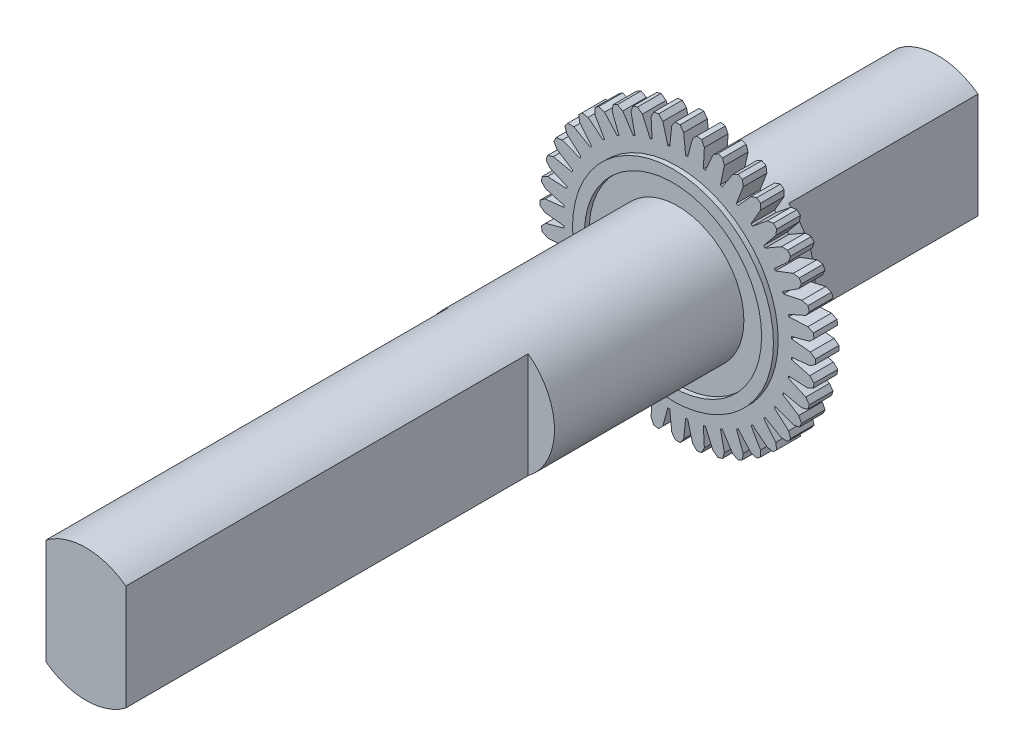
SolidWorks part; units mm, degrees
ref_plane "Front Plane" through (0, 0, 0) normal (0, 0, 1) x (1, 0, 0)
ref_plane "Top Plane" through (0, 0, 0) normal (0, 1, 0) x (1, 0, 0)
ref_plane "Right Plane" through (0, 0, 0) normal (1, 0, 0) x (0, 0, -1)
sketch "Sketch1" plane through (0, 0, 0) normal (0, 0, 1) x (1, 0, 0)
  line L0 (0, 0) -> (0, 5.815) construction
  line L1 (0, 0) -> (0.3359, 4.8033) construction
  line L2 (1.0098, 5.7267) -> (1.1251, 5.4958)
  line L3 (0.1015, 5.8141) -> (0.2515, 5.6041)
  line L4 (0.2515, 5.6041) -> (0.3359, 4.8033)
  line L5 (-0.2515, 5.6041) -> (-0.3359, 4.8033)
  line L6 (-0.1015, 5.8141) -> (-0.2515, 5.6041)
  line L7 (1.1251, 5.4958) -> (1.0831, 4.6916)
  line L8 (0.6283, 5.5745) -> (0.4197, 4.7967)
  line L9 (0.8093, 5.7584) -> (0.6283, 5.5745)
  line L10 (1.8932, 5.4982) -> (1.9709, 5.2521)
  line L11 (1.9709, 5.2521) -> (1.8037, 4.4644)
  line L12 (1.4926, 5.4075) -> (1.1649, 4.672)
  line L13 (1.7001, 5.5609) -> (1.4926, 5.4075)
  line L14 (2.73, 5.1343) -> (2.7683, 4.8791)
  line L15 (2.7683, 4.8791) -> (2.4799, 4.1273)
  line L16 (2.3201, 5.1075) -> (1.8814, 4.4322)
  line L17 (2.5491, 5.2265) -> (2.3201, 5.1075)
  line L18 (3.4996, 4.6441) -> (3.4975, 4.386)
  line L19 (3.4975, 4.386) -> (3.095, 3.6885)
  line L20 (3.0906, 4.6816) -> (2.5516, 4.0834)
  line L21 (3.3353, 4.7634) -> (3.0906, 4.6816)
  line L22 (4.183, 4.0394) -> (4.1405, 3.7849)
  line L23 (4.1405, 3.7849) -> (3.6339, 3.1589)
  line L24 (3.7849, 4.1405) -> (3.1589, 3.6339)
  line L25 (4.0394, 4.183) -> (3.7849, 4.1405)
  line L26 (4.7634, 3.3353) -> (4.6816, 3.0906)
  line L27 (4.6816, 3.0906) -> (4.0834, 2.5516)
  line L28 (4.386, 3.4975) -> (3.6885, 3.095)
  line L29 (4.6441, 3.4996) -> (4.386, 3.4975)
  line L30 (5.2265, 2.5491) -> (5.1075, 2.3201)
  line L31 (5.1075, 2.3201) -> (4.4322, 1.8814)
  line L32 (4.8791, 2.7683) -> (4.1273, 2.4799)
  line L33 (5.1343, 2.73) -> (4.8791, 2.7683)
  line L34 (5.5609, 1.7001) -> (5.4075, 1.4926)
  line L35 (5.4075, 1.4926) -> (4.672, 1.1649)
  line L36 (5.2521, 1.9709) -> (4.4644, 1.8037)
  line L37 (5.4982, 1.8932) -> (5.2521, 1.9709)
  line L38 (5.7584, 0.8093) -> (5.5745, 0.6283)
  line L39 (5.5745, 0.6283) -> (4.7967, 0.4197)
  line L40 (5.4958, 1.1251) -> (4.6916, 1.0831)
  line L41 (5.7267, 1.0098) -> (5.4958, 1.1251)
  line L42 (5.8141, -0.1015) -> (5.6041, -0.2515)
  line L43 (5.6041, -0.2515) -> (4.8033, -0.3359)
  line L44 (5.6041, 0.2515) -> (4.8033, 0.3359)
  line L45 (5.8141, 0.1015) -> (5.6041, 0.2515)
  line L46 (5.7267, -1.0098) -> (5.4958, -1.1251)
  line L47 (5.4958, -1.1251) -> (4.6916, -1.0831)
  line L48 (5.5745, -0.6283) -> (4.7967, -0.4197)
  line L49 (5.7584, -0.8093) -> (5.5745, -0.6283)
  line L50 (5.4982, -1.8932) -> (5.2521, -1.9709)
  line L51 (5.2521, -1.9709) -> (4.4644, -1.8037)
  line L52 (5.4075, -1.4926) -> (4.672, -1.1649)
  line L53 (5.5609, -1.7001) -> (5.4075, -1.4926)
  line L54 (5.1343, -2.73) -> (4.8791, -2.7683)
  line L55 (4.8791, -2.7683) -> (4.1273, -2.4799)
  line L56 (5.1075, -2.3201) -> (4.4322, -1.8814)
  line L57 (5.2265, -2.5491) -> (5.1075, -2.3201)
  line L58 (4.6441, -3.4996) -> (4.386, -3.4975)
  line L59 (4.386, -3.4975) -> (3.6885, -3.095)
  line L60 (4.6816, -3.0906) -> (4.0834, -2.5516)
  line L61 (4.7634, -3.3353) -> (4.6816, -3.0906)
  line L62 (4.0394, -4.183) -> (3.7849, -4.1405)
  line L63 (3.7849, -4.1405) -> (3.1589, -3.6339)
  line L64 (4.1405, -3.7849) -> (3.6339, -3.1589)
  line L65 (4.183, -4.0394) -> (4.1405, -3.7849)
  line L66 (3.3353, -4.7634) -> (3.0906, -4.6816)
  line L67 (3.0906, -4.6816) -> (2.5516, -4.0834)
  line L68 (3.4975, -4.386) -> (3.095, -3.6885)
  line L69 (3.4996, -4.6441) -> (3.4975, -4.386)
  line L70 (2.5491, -5.2265) -> (2.3201, -5.1075)
  line L71 (2.3201, -5.1075) -> (1.8814, -4.4322)
  line L72 (2.7683, -4.8791) -> (2.4799, -4.1273)
  line L73 (2.73, -5.1343) -> (2.7683, -4.8791)
  line L74 (1.7001, -5.5609) -> (1.4926, -5.4075)
  line L75 (1.4926, -5.4075) -> (1.1649, -4.672)
  line L76 (1.9709, -5.2521) -> (1.8037, -4.4644)
  line L77 (1.8932, -5.4982) -> (1.9709, -5.2521)
  line L78 (0.8093, -5.7584) -> (0.6283, -5.5745)
  line L79 (0.6283, -5.5745) -> (0.4197, -4.7967)
  line L80 (1.1251, -5.4958) -> (1.0831, -4.6916)
  line L81 (1.0098, -5.7267) -> (1.1251, -5.4958)
  line L82 (-0.1015, -5.8141) -> (-0.2515, -5.6041)
  line L83 (-0.2515, -5.6041) -> (-0.3359, -4.8033)
  line L84 (0.2515, -5.6041) -> (0.3359, -4.8033)
  line L85 (0.1015, -5.8141) -> (0.2515, -5.6041)
  line L86 (-1.0098, -5.7267) -> (-1.1251, -5.4958)
  line L87 (-1.1251, -5.4958) -> (-1.0831, -4.6916)
  line L88 (-0.6283, -5.5745) -> (-0.4197, -4.7967)
  line L89 (-0.8093, -5.7584) -> (-0.6283, -5.5745)
  line L90 (-1.8932, -5.4982) -> (-1.9709, -5.2521)
  line L91 (-1.9709, -5.2521) -> (-1.8037, -4.4644)
  line L92 (-1.4926, -5.4075) -> (-1.1649, -4.672)
  line L93 (-1.7001, -5.5609) -> (-1.4926, -5.4075)
  line L94 (-2.73, -5.1343) -> (-2.7683, -4.8791)
  line L95 (-2.7683, -4.8791) -> (-2.4799, -4.1273)
  line L96 (-2.3201, -5.1075) -> (-1.8814, -4.4322)
  line L97 (-2.5491, -5.2265) -> (-2.3201, -5.1075)
  line L98 (-3.4996, -4.6441) -> (-3.4975, -4.386)
  line L99 (-3.4975, -4.386) -> (-3.095, -3.6885)
  line L100 (-3.0906, -4.6816) -> (-2.5516, -4.0834)
  line L101 (-3.3353, -4.7634) -> (-3.0906, -4.6816)
  line L102 (-4.183, -4.0394) -> (-4.1405, -3.7849)
  line L103 (-4.1405, -3.7849) -> (-3.6339, -3.1589)
  line L104 (-3.7849, -4.1405) -> (-3.1589, -3.6339)
  line L105 (-4.0394, -4.183) -> (-3.7849, -4.1405)
  line L106 (-4.7634, -3.3353) -> (-4.6816, -3.0906)
  line L107 (-4.6816, -3.0906) -> (-4.0834, -2.5516)
  line L108 (-4.386, -3.4975) -> (-3.6885, -3.095)
  line L109 (-4.6441, -3.4996) -> (-4.386, -3.4975)
  line L110 (-5.2265, -2.5491) -> (-5.1075, -2.3201)
  line L111 (-5.1075, -2.3201) -> (-4.4322, -1.8814)
  line L112 (-4.8791, -2.7683) -> (-4.1273, -2.4799)
  line L113 (-5.1343, -2.73) -> (-4.8791, -2.7683)
  line L114 (-5.5609, -1.7001) -> (-5.4075, -1.4926)
  line L115 (-5.4075, -1.4926) -> (-4.672, -1.1649)
  line L116 (-5.2521, -1.9709) -> (-4.4644, -1.8037)
  line L117 (-5.4982, -1.8932) -> (-5.2521, -1.9709)
  line L118 (-5.7584, -0.8093) -> (-5.5745, -0.6283)
  line L119 (-5.5745, -0.6283) -> (-4.7967, -0.4197)
  line L120 (-5.4958, -1.1251) -> (-4.6916, -1.0831)
  line L121 (-5.7267, -1.0098) -> (-5.4958, -1.1251)
  line L122 (-5.8141, 0.1015) -> (-5.6041, 0.2515)
  line L123 (-5.6041, 0.2515) -> (-4.8033, 0.3359)
  line L124 (-5.6041, -0.2515) -> (-4.8033, -0.3359)
  line L125 (-5.8141, -0.1015) -> (-5.6041, -0.2515)
  line L126 (-5.7267, 1.0098) -> (-5.4958, 1.1251)
  line L127 (-5.4958, 1.1251) -> (-4.6916, 1.0831)
  line L128 (-5.5745, 0.6283) -> (-4.7967, 0.4197)
  line L129 (-5.7584, 0.8093) -> (-5.5745, 0.6283)
  line L130 (-5.4982, 1.8932) -> (-5.2521, 1.9709)
  line L131 (-5.2521, 1.9709) -> (-4.4644, 1.8037)
  line L132 (-5.4075, 1.4926) -> (-4.672, 1.1649)
  line L133 (-5.5609, 1.7001) -> (-5.4075, 1.4926)
  line L134 (-5.1343, 2.73) -> (-4.8791, 2.7683)
  line L135 (-4.8791, 2.7683) -> (-4.1273, 2.4799)
  line L136 (-5.1075, 2.3201) -> (-4.4322, 1.8814)
  line L137 (-5.2265, 2.5491) -> (-5.1075, 2.3201)
  line L138 (-4.6441, 3.4996) -> (-4.386, 3.4975)
  line L139 (-4.386, 3.4975) -> (-3.6885, 3.095)
  line L140 (-4.6816, 3.0906) -> (-4.0834, 2.5516)
  line L141 (-4.7634, 3.3353) -> (-4.6816, 3.0906)
  line L142 (-4.0394, 4.183) -> (-3.7849, 4.1405)
  line L143 (-3.7849, 4.1405) -> (-3.1589, 3.6339)
  line L144 (-4.1405, 3.7849) -> (-3.6339, 3.1589)
  line L145 (-4.183, 4.0394) -> (-4.1405, 3.7849)
  line L146 (-3.3353, 4.7634) -> (-3.0906, 4.6816)
  line L147 (-3.0906, 4.6816) -> (-2.5516, 4.0834)
  line L148 (-3.4975, 4.386) -> (-3.095, 3.6885)
  line L149 (-3.4996, 4.6441) -> (-3.4975, 4.386)
  line L150 (-2.5491, 5.2265) -> (-2.3201, 5.1075)
  line L151 (-2.3201, 5.1075) -> (-1.8814, 4.4322)
  line L152 (-2.7683, 4.8791) -> (-2.4799, 4.1273)
  line L153 (-2.73, 5.1343) -> (-2.7683, 4.8791)
  line L154 (-1.7001, 5.5609) -> (-1.4926, 5.4075)
  line L155 (-1.4926, 5.4075) -> (-1.1649, 4.672)
  line L156 (-1.9709, 5.2521) -> (-1.8037, 4.4644)
  line L157 (-1.8932, 5.4982) -> (-1.9709, 5.2521)
  line L158 (-0.8093, 5.7584) -> (-0.6283, 5.5745)
  line L159 (-0.6283, 5.5745) -> (-0.4197, 4.7967)
  line L160 (-1.1251, 5.4958) -> (-1.0831, 4.6916)
  line L161 (-1.0098, 5.7267) -> (-1.1251, 5.4958)
  arc A0 (0.1015, 5.8141) -> (-0.1015, 5.8141) centre (0, 0) ccw
  arc A1 (-2.4799, 4.1273) -> (-2.5516, 4.0834) centre (0, 0) ccw
  arc A2 (1.0098, 5.7267) -> (0.8093, 5.7584) centre (0, 0) ccw
  circle A3 centre (0, 0) radius 5.815 construction
  arc A4 (1.8932, 5.4982) -> (1.7001, 5.5609) centre (0, 0) ccw
  arc A5 (2.73, 5.1343) -> (2.5491, 5.2265) centre (0, 0) ccw
  arc A6 (3.4996, 4.6441) -> (3.3353, 4.7634) centre (0, 0) ccw
  arc A7 (4.183, 4.0394) -> (4.0394, 4.183) centre (0, 0) ccw
  arc A8 (4.7634, 3.3353) -> (4.6441, 3.4996) centre (0, 0) ccw
  arc A9 (5.2265, 2.5491) -> (5.1343, 2.73) centre (0, 0) ccw
  arc A10 (5.5609, 1.7001) -> (5.4982, 1.8932) centre (0, 0) ccw
  arc A11 (5.7584, 0.8093) -> (5.7267, 1.0098) centre (0, 0) ccw
  arc A12 (5.8141, -0.1015) -> (5.8141, 0.1015) centre (0, 0) ccw
  arc A13 (5.7267, -1.0098) -> (5.7584, -0.8093) centre (0, 0) ccw
  arc A14 (5.4982, -1.8932) -> (5.5609, -1.7001) centre (0, 0) ccw
  arc A15 (5.1343, -2.73) -> (5.2265, -2.5491) centre (0, 0) ccw
  arc A16 (4.6441, -3.4996) -> (4.7634, -3.3353) centre (0, 0) ccw
  arc A17 (4.0394, -4.183) -> (4.183, -4.0394) centre (0, 0) ccw
  arc A18 (3.3353, -4.7634) -> (3.4996, -4.6441) centre (0, 0) ccw
  arc A19 (2.5491, -5.2265) -> (2.73, -5.1343) centre (0, 0) ccw
  arc A20 (1.7001, -5.5609) -> (1.8932, -5.4982) centre (0, 0) ccw
  arc A21 (0.8093, -5.7584) -> (1.0098, -5.7267) centre (0, 0) ccw
  arc A22 (-0.1015, -5.8141) -> (0.1015, -5.8141) centre (0, 0) ccw
  arc A23 (-1.0098, -5.7267) -> (-0.8093, -5.7584) centre (0, 0) ccw
  arc A24 (-1.8932, -5.4982) -> (-1.7001, -5.5609) centre (0, 0) ccw
  arc A25 (-2.73, -5.1343) -> (-2.5491, -5.2265) centre (0, 0) ccw
  arc A26 (-3.4996, -4.6441) -> (-3.3353, -4.7634) centre (0, 0) ccw
  arc A27 (-4.183, -4.0394) -> (-4.0394, -4.183) centre (0, 0) ccw
  arc A28 (-4.7634, -3.3353) -> (-4.6441, -3.4996) centre (0, 0) ccw
  arc A29 (-5.2265, -2.5491) -> (-5.1343, -2.73) centre (0, 0) ccw
  arc A30 (-5.5609, -1.7001) -> (-5.4982, -1.8932) centre (0, 0) ccw
  arc A31 (-5.7584, -0.8093) -> (-5.7267, -1.0098) centre (0, 0) ccw
  arc A32 (-5.8141, 0.1015) -> (-5.8141, -0.1015) centre (0, 0) ccw
  arc A33 (-5.7267, 1.0098) -> (-5.7584, 0.8093) centre (0, 0) ccw
  arc A34 (-5.4982, 1.8932) -> (-5.5609, 1.7001) centre (0, 0) ccw
  arc A35 (-5.1343, 2.73) -> (-5.2265, 2.5491) centre (0, 0) ccw
  arc A36 (-4.6441, 3.4996) -> (-4.7634, 3.3353) centre (0, 0) ccw
  arc A37 (-4.0394, 4.183) -> (-4.183, 4.0394) centre (0, 0) ccw
  arc A38 (-3.3353, 4.7634) -> (-3.4996, 4.6441) centre (0, 0) ccw
  arc A39 (-2.5491, 5.2265) -> (-2.73, 5.1343) centre (0, 0) ccw
  arc A40 (-1.7001, 5.5609) -> (-1.8932, 5.4982) centre (0, 0) ccw
  arc A41 (-0.8093, 5.7584) -> (-1.0098, 5.7267) centre (0, 0) ccw
  arc A42 (-1.8037, 4.4644) -> (-1.8814, 4.4322) centre (0, 0) ccw
  circle A43 centre (0, 0) radius 4.815 construction
  arc A44 (-1.0831, 4.6916) -> (-1.1649, 4.672) centre (0, 0) ccw
  arc A45 (-0.3359, 4.8033) -> (-0.4197, 4.7967) centre (0, 0) ccw
  arc A46 (0.4197, 4.7967) -> (0.3359, 4.8033) centre (0, 0) ccw
  arc A47 (1.1649, 4.672) -> (1.0831, 4.6916) centre (0, 0) ccw
  arc A48 (1.8814, 4.4322) -> (1.8037, 4.4644) centre (0, 0) ccw
  arc A49 (2.5516, 4.0834) -> (2.4799, 4.1273) centre (0, 0) ccw
  arc A50 (3.1589, 3.6339) -> (3.095, 3.6885) centre (0, 0) ccw
  arc A51 (3.6885, 3.095) -> (3.6339, 3.1589) centre (0, 0) ccw
  arc A52 (4.1273, 2.4799) -> (4.0834, 2.5516) centre (0, 0) ccw
  arc A53 (4.4644, 1.8037) -> (4.4322, 1.8814) centre (0, 0) ccw
  arc A54 (4.6916, 1.0831) -> (4.672, 1.1649) centre (0, 0) ccw
  arc A55 (4.8033, 0.3359) -> (4.7967, 0.4197) centre (0, 0) ccw
  arc A56 (4.7967, -0.4197) -> (4.8033, -0.3359) centre (0, 0) ccw
  arc A57 (4.672, -1.1649) -> (4.6916, -1.0831) centre (0, 0) ccw
  arc A58 (4.4322, -1.8814) -> (4.4644, -1.8037) centre (0, 0) ccw
  arc A59 (4.0834, -2.5516) -> (4.1273, -2.4799) centre (0, 0) ccw
  arc A60 (3.6339, -3.1589) -> (3.6885, -3.095) centre (0, 0) ccw
  arc A61 (3.095, -3.6885) -> (3.1589, -3.6339) centre (0, 0) ccw
  arc A62 (2.4799, -4.1273) -> (2.5516, -4.0834) centre (0, 0) ccw
  arc A63 (1.8037, -4.4644) -> (1.8814, -4.4322) centre (0, 0) ccw
  arc A64 (1.0831, -4.6916) -> (1.1649, -4.672) centre (0, 0) ccw
  arc A65 (0.3359, -4.8033) -> (0.4197, -4.7967) centre (0, 0) ccw
  arc A66 (-0.4197, -4.7967) -> (-0.3359, -4.8033) centre (0, 0) ccw
  arc A67 (-1.1649, -4.672) -> (-1.0831, -4.6916) centre (0, 0) ccw
  arc A68 (-1.8814, -4.4322) -> (-1.8037, -4.4644) centre (0, 0) ccw
  arc A69 (-2.5516, -4.0834) -> (-2.4799, -4.1273) centre (0, 0) ccw
  arc A70 (-3.1589, -3.6339) -> (-3.095, -3.6885) centre (0, 0) ccw
  arc A71 (-3.6885, -3.095) -> (-3.6339, -3.1589) centre (0, 0) ccw
  arc A72 (-4.1273, -2.4799) -> (-4.0834, -2.5516) centre (0, 0) ccw
  arc A73 (-4.4644, -1.8037) -> (-4.4322, -1.8814) centre (0, 0) ccw
  arc A74 (-4.6916, -1.0831) -> (-4.672, -1.1649) centre (0, 0) ccw
  arc A75 (-4.8033, -0.3359) -> (-4.7967, -0.4197) centre (0, 0) ccw
  arc A76 (-4.7967, 0.4197) -> (-4.8033, 0.3359) centre (0, 0) ccw
  arc A77 (-4.672, 1.1649) -> (-4.6916, 1.0831) centre (0, 0) ccw
  arc A78 (-4.4322, 1.8814) -> (-4.4644, 1.8037) centre (0, 0) ccw
  arc A79 (-4.0834, 2.5516) -> (-4.1273, 2.4799) centre (0, 0) ccw
  arc A80 (-3.6339, 3.1589) -> (-3.6885, 3.095) centre (0, 0) ccw
  arc A81 (-3.095, 3.6885) -> (-3.1589, 3.6339) centre (0, 0) ccw
  point P5 (5.5609, 1.7001)
  point P9 (4.815, 0)
  point P250 (0, 0)
  dimension "D1" = 11.63
  dimension "D3" = 4
  dimension "D4" = 40
  dimension "D5" = 0.21
  dimension "D6" = 0.8008
  dimension "D2" = 1
extrude "Boss-Extrude1" add sketch "Sketch1" along normal blind 1
sketch "Sketch2" plane through (0, 0, 1) normal (0, 0, 1) x (1, 0, 0)
  circle A0 centre (0, 0) radius 5.815 construction
  circle A1 centre (0, 0) radius 4.245
  circle A2 centre (0, 0) radius 3.745
  dimension "D1" = 1.57
  dimension "D2" = 0.5
extrude "Boss-Extrude2" add sketch "Sketch2" along normal blind 0.2
sketch "Sketch3" plane through (0, 0, 1) normal (0, 0, 1) x (1, 0, 0)
  circle A0 centre (0, 0) radius 2.795
  dimension "D1" = 5.59
extrude "Boss-Extrude3" add sketch "Sketch3" along normal blind 25
sketch "Sketch4" plane through (0, 0, 0) normal (0, 0, -1) x (-1, 0, 0)
  circle A0 centre (0, 0) radius 2.795 construction
  circle A1 centre (0, 0) radius 2.795
extrude "Boss-Extrude4" add sketch "Sketch4" along normal blind 2
sketch "Sketch6" plane through (0, 0, 26) normal (0, 0, 1) x (1, 0, 0)
  line L0 (-1.685, 2.795) -> (-3.331, 0.7139)
  line L2 (1.685, -2.795) -> (1.685, 2.795)
  line L4 (-1.685, -2.795) -> (-1.685, 2.795)
  line L5 (-3.331, 0.7139) -> (-3.0893, -1.201)
  line L6 (-3.0893, -1.201) -> (-1.685, -2.795)
  line L7 (1.685, 2.795) -> (3.5183, 0.7139)
  line L8 (3.5183, 0.7139) -> (3.2132, -0.9593)
  line L9 (3.2132, -0.9593) -> (1.685, -2.795)
  point P0 (0, 0)
  dimension "D1" = 3.37
extrude "Cut-Extrude2" cut sketch "Sketch6" against normal blind 17
sketch "Sketch7" plane through (0, 0, -2) normal (0, 0, -1) x (-1, 0, 0)
  line L2 (1.685, -2.23) -> (1.685, 2.23)
  line L3 (-1.685, 2.23) -> (-1.685, -2.23)
  line L4 (1.685, -2.23) -> (1.685, 2.23)
  line L5 (-1.685, 2.23) -> (-1.685, -2.23)
  arc A2 (-1.685, -2.23) -> (1.685, -2.23) centre (0, 0) ccw
  arc A3 (1.685, 2.23) -> (-1.685, 2.23) centre (0, 0) ccw
  arc A4 (-1.685, -2.23) -> (1.685, -2.23) centre (0, 0) ccw
  arc A5 (1.685, 2.23) -> (-1.685, 2.23) centre (0, 0) ccw
  dimension "D1" = 0
extrude "Boss-Extrude5" add sketch "Sketch7" along normal blind 8
